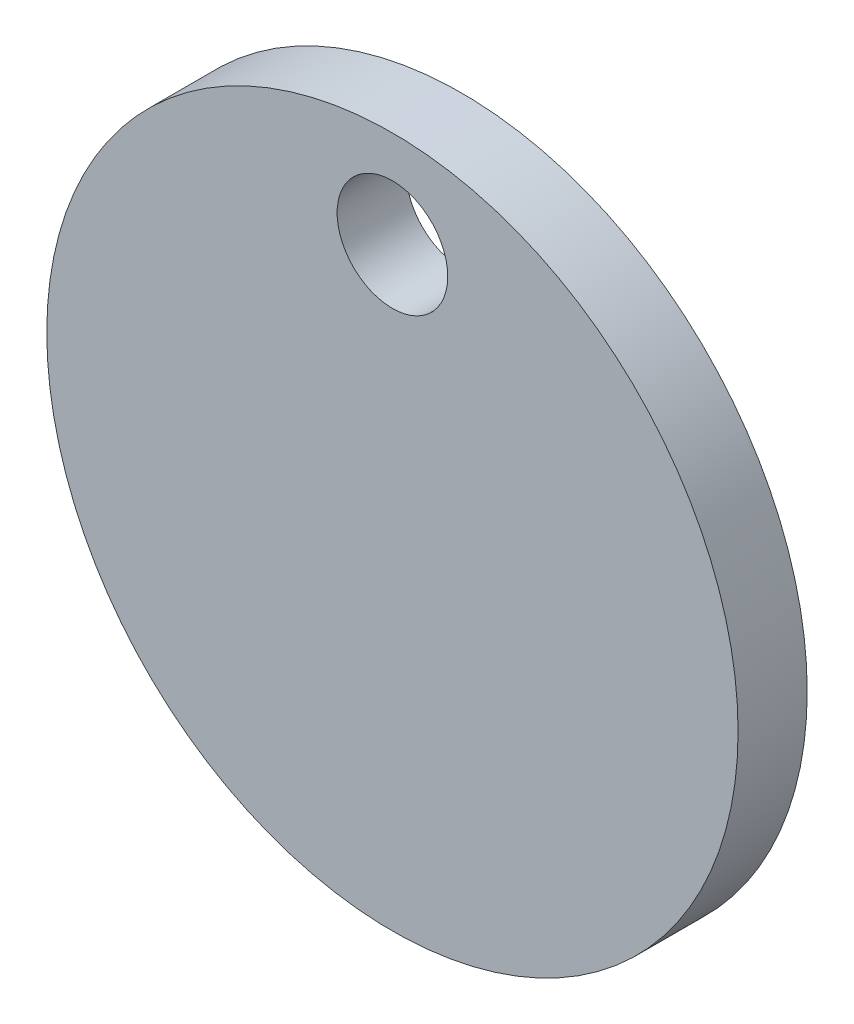
SolidWorks part; units mm, degrees
ref_plane "Front Plane" through (0, 0, 0) normal (0, 0, 1) x (1, 0, 0)
ref_plane "Top Plane" through (0, 0, 0) normal (0, 1, 0) x (1, 0, 0)
ref_plane "Right Plane" through (0, 0, 0) normal (1, 0, 0) x (0, 0, -1)
sketch "Sketch1" plane through (0, 0, 0) normal (0, 0, 1) x (1, 0, 0)
  circle A0 centre (0, 0) radius 50
extrude "Boss-Extrude1" add sketch "Sketch1" along normal blind 10
sketch "Sketch2" plane through (0, 0, 10) normal (0, 0, 1) x (1, 0, 0)
  circle A0 centre (0, 36) radius 8
  dimension "D1" = 36
extrude "Cut-Extrude1" cut sketch "Sketch2" against normal through all
